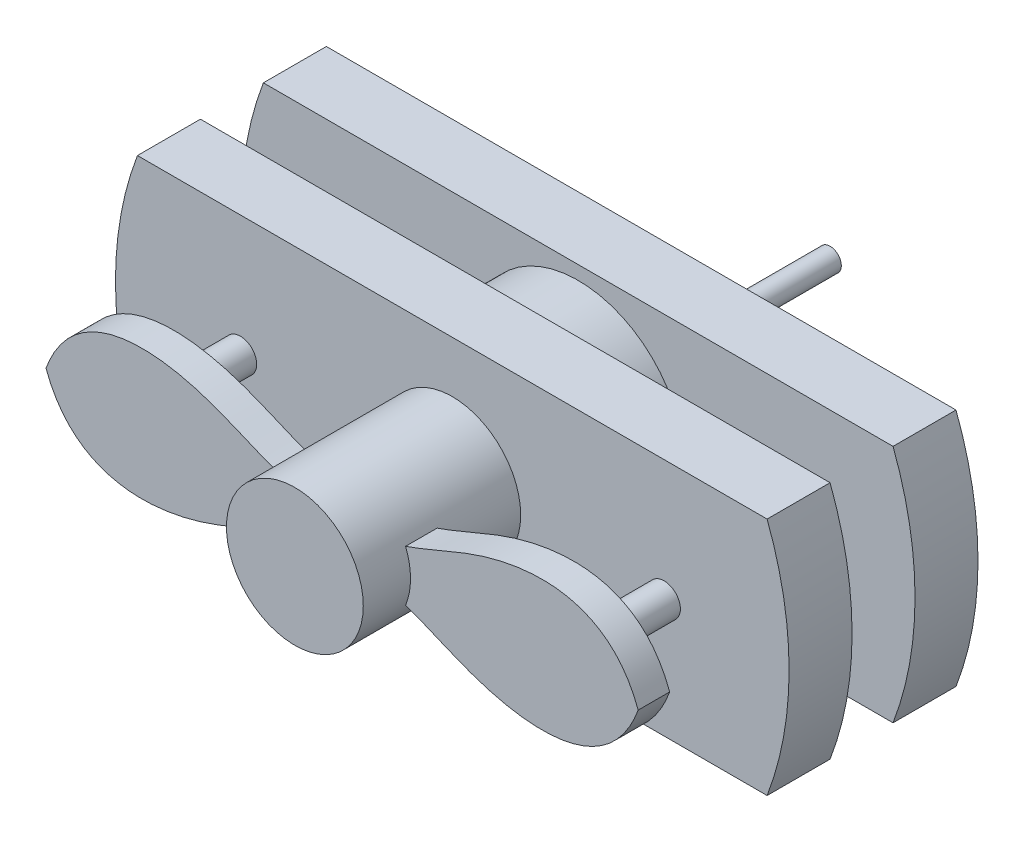
SolidWorks part; units mm, degrees
ref_plane "Front Plane" through (0, 0, 0) normal (0, 0, 1) x (1, 0, 0)
ref_plane "Top Plane" through (0, 0, 0) normal (0, 1, 0) x (1, 0, 0)
ref_plane "Right Plane" through (0, 0, 0) normal (1, 0, 0) x (0, 0, -1)
sketch "Sketch1" plane through (0, 0, 0) normal (0, 0, 1) x (1, 0, 0)
  line L0 (12.7, 16.2338) -> (12.7, -8.0341) construction
  line L1 (0, 0) -> (25.4, 0)
  line L3 (0, 9.6589) -> (25.4, 9.6589)
  arc A0 (0, 9.6589) -> (0, 0) centre (12.7, 4.8295) ccw
  arc A1 (25.4, 9.6589) -> (25.4, 0) centre (12.7, 4.8295) cw
  dimension "D1" = 25.4
extrude "Boss-Extrude1" add sketch "Sketch1" along normal blind 2.54
sketch "Sketch2" plane through (0, 0, 2.54) normal (0, 0, 1) x (1, 0, 0)
  line L0 (12.7, 11.2695) -> (12.7, -2.374) construction
  line L1 (-1.8056, 4.8295) -> (29.3481, 4.8295) construction
  circle A0 centre (12.7, 4.8295) radius 4.2772
extrude "Boss-Extrude2" add sketch "Sketch2" along normal blind 2.54
sketch "Sketch4" plane through (0, 0, 2.54) normal (0, 0, 1) x (1, 0, 0)
  line L0 (25.4, 0) -> (0, 0)
  line L1 (25.4, 9.6589) -> (0, 9.6589)
  arc A0 (0, 0) -> (0, 9.6589) centre (12.7, 4.8295) cw
  arc A1 (25.4, 0) -> (25.4, 9.6589) centre (12.7, 4.8295) ccw
extrude "Boss-Extrude3" add sketch "Sketch4" along normal blind 2.54 from surface at 2.54 starting at face at (16.9772, 4.8295, 5.08)
sketch "Sketch5" plane through (0, 0, 7.62) normal (0, 0, 1) x (1, 0, 0)
  line L0 (12.7, -1.8569) -> (12.7, 10.6785) construction
  line L1 (27.6735, 4.8295) -> (-3.825, 4.8295) construction
  spline S0 degree 3 poles (12.7, 4.2015) (14.8107, 4.3187) (18.3387, 1.8792) (23.5399, 1.8287) (24.6443, 4.8295) knots 0 0 0 0 0.434444 1 1 1 1
  spline S1 degree 3 poles (12.7, 5.4575) (14.8107, 5.3403) (18.3387, 7.7798) (23.5399, 7.8302) (24.6443, 4.8295) knots 0 0 0 0 0.434444 1 1 1 1
  spline S2 degree 3 poles (12.7, 5.4575) (10.5893, 5.3403) (7.0613, 7.7798) (1.8601, 7.8302) (0.7557, 4.8295) knots 0 0 0 0 0.434444 1 1 1 1
  spline S3 degree 3 poles (12.7, 4.2015) (10.5893, 4.3187) (7.0613, 1.8792) (1.8601, 1.8287) (0.7557, 4.8295) knots 0 0 0 0 0.434444 1 1 1 1
extrude "Boss-Extrude4" add sketch "Sketch5" along normal blind 1.27 from offset 3.175 separate body
sketch "Sketch6" plane through (0, 0, 12.065) normal (0, 0, 1) x (1, 0, 0)
  line L0 (12.7, -0.6994) -> (12.7, 11.4173) construction
  circle A0 centre (21.2457, 4.7679) radius 0.6558
  circle A1 centre (4.1543, 4.7679) radius 0.6558
extrude "Boss-Extrude5" add sketch "Sketch6" against normal up to surface (9.525 mm away)
sketch "Sketch7" plane through (0, 0, 7.62) normal (0, 0, 1) x (1, 0, 0)
  line L0 (12.7, -1.2412) -> (12.7, 11.3434) construction
  line L1 (-1.8302, 4.8295) -> (27.969, 4.8295) construction
  circle A0 centre (12.7, 4.8295) radius 2.7596
extrude "Boss-Extrude6" add sketch "Sketch7" along normal blind 6.35
sketch "Sketch8" plane through (0, 0, 0) normal (0, 0, -1) x (-1, 0, 0)
  line L0 (-12.7, -1.1) -> (-12.7, 10.6357) construction
  line L1 (1.9943, 4.8295) -> (-27.5422, 4.8295) construction
  circle A0 centre (-12.7, 4.7678) radius 0.4533
extrude "Boss-Extrude7" add sketch "Sketch8" along normal blind 7.62
